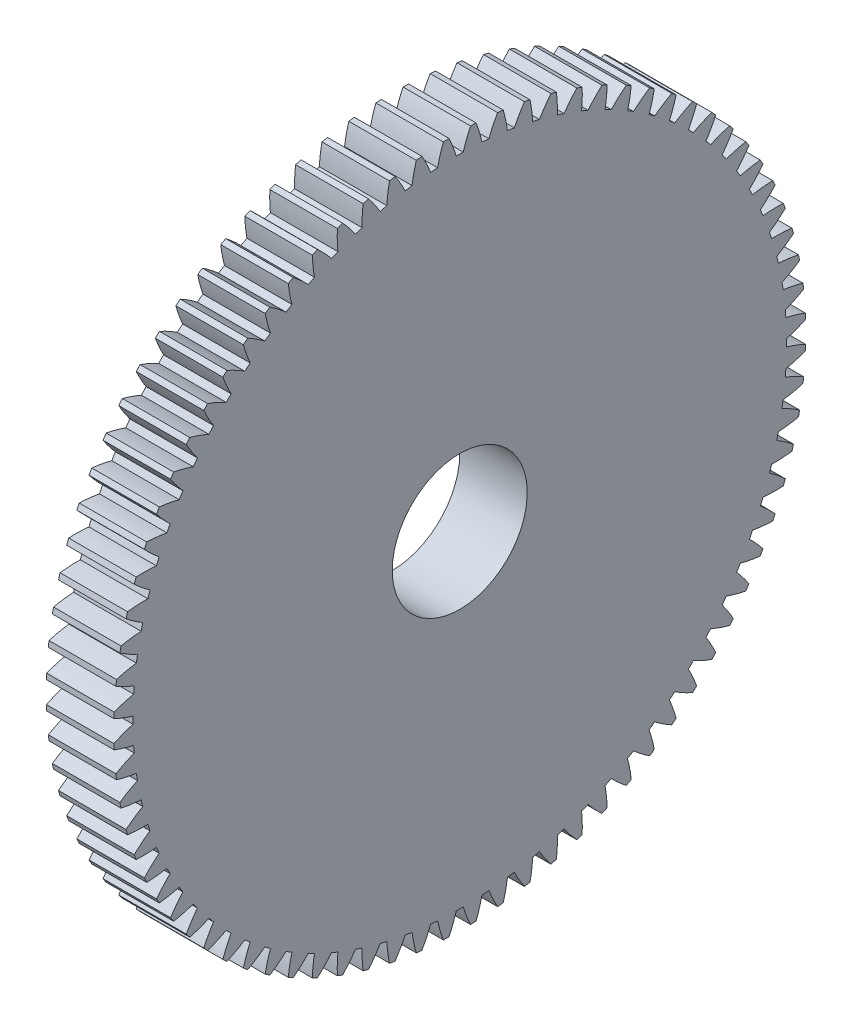
SolidWorks part; units mm, degrees
ref_plane "Plane1" through (0, 0, 0) normal (0, 0, 1) x (1, 0, 0)
ref_plane "Plane2" through (0, 0, 0) normal (0, 1, 0) x (1, 0, 0)
ref_plane "Plane3" through (0, 0, 0) normal (1, 0, 0) x (0, 0, -1)
sketch "HoldingSke" plane through (0, 0, 0) normal (0, 1, 0) x (1, 0, 0)
  line L0 (0, 0) -> (141.1412, -800.4517)
  line L1 (-15, 0) -> (100, 0) construction
  line L2 (0, 0) -> (-2.1039, 2.3779)
  line L3 (0, 0) -> (-11.863, 4.5341)
  line L4 (0, 0) -> (1.4996, 8.5048)
  line L5 (0, 0) -> (-47.5972, -17.7524)
  line L6 (0, 0) -> (-5.2639, -3.5516)
  line L7 (-2.1039, 2.3779) -> (8.8308, 51.9871)
  line L8 (-76.2, 54.61) -> (-61.976, 54.61)
  line L9 (-71.009, 38.7566) -> (-53.1078, 45.2721)
  line L10 (-76.2, 71.12) -> (104.1128, 71.12)
  line L11 (0, 0) -> (-6.35, 0)
  line L12 (-76.2, 101.6) -> (-76.1716, 101.6)
  line L13 (24.9733, 27.94) -> (52.9518, 28.4284)
  line L14 (24.9733, 27.94) -> (25.0241, 27.9398)
  line L15 (24.9733, 27.94) -> (100.4021, 29.52)
  circle A0 centre (0, 0) radius 6.35
  circle A1 centre (0, 0) radius 30.7467
  circle A2 centre (0, 0) radius 38.1
  circle A3 centre (0, 0) radius 6.35
  dimension "MHD" = 61.4934
  dimension "Hub_dia" = 76.2
  dimension "Bore" = 12.7
  dimension "MBD" = 12.7
  dimension "Num_teeth" = 80
  dimension "Pitch" = 812.8
  dimension "Overall_len" = 50.8
  dimension "Show_teeth" = 80
  dimension "Thickness" = 6.35
  dimension "OAL" = 50.8001
  dimension "T_dim" = 14.224
  dimension "Ap" = 20
  dimension "H" = 19.05
  dimension "Pitch_radius" = 180.3128
  dimension "Width" = 6.35
  dimension "Backlash" = 0.0284
  dimension "Addendum_fac" = 1
  dimension "Dedendum_fac" = 1.2
  dimension "Clearance_fac" = 0.2
  dimension "Dedendum_add" = 0.0508
sketch "BasProSke" plane through (0, 0, 0) normal (0, 1, 0) x (1, 0, 0)
  line L0 (-10, 0) -> (60, 0) construction
  line L1 (0, 0) -> (0, 32.5437)
  line L2 (0, 0) -> (6.35, 0)
  line L3 (6.35, 0) -> (6.35, 32.5437)
  line L4 (6.35, 32.5437) -> (0, 32.5437)
  dimension "Thickness" = 6.35
  dimension "Diameter" = 65.0875
revolve "Base-Revolve" add sketch "BasProSke" angle 360 about L0
sketch "TooCutSke" plane through (0, 0, 0) normal (1, 0, 0) x (0, 0, -1)
  line L1 (0, 0) -> (0, 107) construction
  line L2 (0, 0) -> (-0.6732, 31.7429) construction
  line L3 (0, 0) -> (-2.4926, 63.4407) construction
  line L4 (-0.6732, 31.7429) -> (-1.2463, 31.7203) construction
  arc A0 (0.3278, 30.745) -> (-0.3278, 30.745) centre (0, 0) ccw
  arc A1 (1.0248, 32.553) -> (-1.0248, 32.553) centre (0, 0) ccw
  circle A2 centre (0, 0) radius 31.75 construction
  circle A3 centre (0, 0) radius 29.8352 construction
  arc A4 (-0.3278, 30.745) -> (-1.0248, 32.553) centre (-12.4918, 27.0942) ccw
  arc A5 (1.0248, 32.553) -> (0.3278, 30.745) centre (12.4918, 27.0942) ccw
  dimension "Root_dia" = 61.4934
  dimension "Overcut_dia" = 65.1383
  dimension "Pitch_dia" = 63.5
  dimension "Base_dia" = 59.6705
  dimension "Flank_rad" = 12.7
  dimension "Half_ang" = 2.25
  dimension "Half_CT" = 0.5736
extrude "ToothCut" cut sketch "TooCutSke" along normal through all
fillet "Breaks" [suppressed] radius 0.0159
fillet "RootFillets" [suppressed] radius 0.2095
pattern_circular "TeethCuts" count 80 every 4.5 about axis through (-10, 0, 0) along (1, 0, 0) of "ToothCut", "RootFillets", "Breaks"
sketch "HubNeaOneSke" plane through (0, 0, 0) normal (-1, 0, 0) x (0, 0, 1)
  circle A0 centre (0, 0) radius 30.7467
  dimension "Diameter" = 61.4934
extrude "HubNearOne" [suppressed] add sketch "HubNeaOneSke" along normal blind 44.4501
sketch "HubNeaBotSke" plane through (0, 0, 0) normal (-1, 0, 0) x (0, 0, 1)
  circle A0 centre (0, 0) radius 30.7467
  dimension "Diameter" = 61.4934
extrude "HubNearBoth" [suppressed] add sketch "HubNeaBotSke" along normal blind 22.225
ref_plane "FarPln" through (6.35, 0, 0) normal (1, 0, 0) x (0, 0, -1)
sketch "HubFarSke" plane through (6.35, 0, 0) normal (1, 0, 0) x (0, 0, -1)
  circle A0 centre (0, 0) radius 30.7467
  dimension "Diameter" = 61.4934
extrude "HubFar" [suppressed] add sketch "HubFarSke" along normal blind 22.225
sketch "BorSke" plane through (0, 0, 0) normal (1, 0, 0) x (0, 0, -1)
  circle A0 centre (0, 0) radius 6.35
  dimension "Diameter" = 12.7
extrude "Bore" cut sketch "BorSke" along normal mid plane 101.6001
sketch "KeySke" plane through (0, 0, 0) normal (1, 0, 0) x (0, 0, -1)
  line L0 (-1.5875, 0) -> (-1.5875, 7.874)
  line L1 (-1.5875, 7.874) -> (1.5875, 7.874)
  line L2 (1.5875, 7.874) -> (1.5875, 0)
  line L3 (0, 0) -> (0, 34) construction
  line L4 (-1.5875, 0) -> (1.5875, 0)
  dimension "Offset" = 7.874
  dimension "Width" = 3.175
extrude "Keyway" [suppressed] cut sketch "KeySke" along normal mid plane 101.6001
pattern_circular "Keyway2" [suppressed] count 2 every 90 about axis through (-10, 0, 0) along (1, 0, 0)
equation "' \"Pitch@HoldingSke\" = 4"
equation "' \"Num_teeth@HoldingSke\" = 12"
equation "' \"Ap@HoldingSke\" =  20"
equation "' \"Ap@HoldingSke\" = 20"
equation "' \"Width@HoldingSke\" = 0.5"
equation "' \"Hub_dia@HoldingSke\"= 1"
equation "' \"Hub_dia@HoldingSke\" = 1"
equation "' \"Overall_len@HoldingSke\" = 1.0"
equation "' \"Bore@HoldingSke\" = 0.75"
equation "' \"T_dim@HoldingSke\" = 0.85"
equation "' \"Width@KeySke\" = 0.25"
equation "' \"Show_teeth@HoldingSke\" = 13"
equation "' \"Backlash@HoldingSke\" = 0.009"
equation "' \"Addendum_fac@HoldingSke\" = 1.0"
equation "' \"Dedendum_fac@HoldingSke\" = 1.25"
equation "' \"Dedendum_add@HoldingSke\" = 0.00005"
equation "' \"Clearance_fac@HoldingSke\" = 0.25"
equation "' \"Pitch@HoldingSke\" = 0.5"
equation "' \"Num_teeth@HoldingSke\" = 23"
equation "' \"Show_teeth@HoldingSke\" = 23"
equation "' \"Backlash@HoldingSke\" = 0.0375"
equation "\"Overcut_dia@TooCutSke\" = (\"Num_teeth@HoldingSke\" + 2 * \"Addendum_fac@HoldingSke\") / \"Pitch@HoldingSke\" + 0.002"
equation "\"Pitch_dia@TooCutSke\" = \"Num_teeth@HoldingSke\" / \"Pitch@HoldingSke\""
equation "\"Base_dia@TooCutSke\" = \"Num_teeth@HoldingSke\" / \"Pitch@HoldingSke\" * cos((\"Ap@HoldingSke\"  * 3.14159265 / 180))"
equation "\"Root_dia@TooCutSke\" = (\"Num_teeth@HoldingSke\" + 2) / \"Pitch@HoldingSke\" - 2 * (\"Addendum_fac@HoldingSke\" + \"Dedendum_fac@HoldingSke\") / \"Pitch@HoldingSke\" - \"Dedendum_add@HoldingSke\" * 2"
equation "\"Half_ang@TooCutSke\" = 180 / \"Num_teeth@HoldingSke\""
equation "\"Half_CT@TooCutSke\" = \"Num_teeth@HoldingSke\" / \"Pitch@HoldingSke\" * sin((3.14159265 / 2 / \"Num_teeth@HoldingSke\")) / 2 - 7 * \"Backlash@HoldingSke\" / 4"
equation "\"Flank_rad@TooCutSke\" = \"Num_teeth@HoldingSke\" / \"Pitch@HoldingSke\" / 5"
equation "\"Radius@RootFillets\" = \"Clearance_fac@HoldingSke\" / \"Pitch@HoldingSke\" + \"Dedendum_add@HoldingSke\""
equation "\"Break_rad@Breaks\" = 0.02 / \"Pitch@HoldingSke\""
equation "\"Thickness@HoldingSke\" = \"Width@HoldingSke\""
equation "\"OAL@HoldingSke\" = \"Thickness@HoldingSke\""
equation "\"MHD@HoldingSke\" = (\"Num_teeth@HoldingSke\" + 2) / \"Pitch@HoldingSke\" - 2 * (\"Addendum_fac@HoldingSke\" + \"Dedendum_fac@HoldingSke\")  / \"Pitch@HoldingSke\" - \"Dedendum_add@HoldingSke\" * 2"
equation "\"MBD@HoldingSke\" = (\"Num_teeth@HoldingSke\" + 2) / \"Pitch@HoldingSke\" - 2 * (\"Addendum_fac@HoldingSke\" + \"Dedendum_fac@HoldingSke\")  / \"Pitch@HoldingSke\" - \"Dedendum_add@HoldingSke\" * 2 - 0.002"
equation "\"MHD@HoldingSke\" = ((sgn( \"MHD@HoldingSke\" - \"Hub_dia@HoldingSke\" )-1)*( \"MHD@HoldingSke\" - \"Hub_dia@HoldingSke\" ))/-2+ \"Hub_dia@HoldingSke\""
equation "\"MBD@HoldingSke\" = ((sgn( \"MBD@HoldingSke\" - \"Bore@HoldingSke\" )-1)*( \"MBD@HoldingSke\" - \"Bore@HoldingSke\" ))/-2+ \"Bore@HoldingSke\""
equation "\"OAL@HoldingSke\" = ((sgn( \"OAL@HoldingSke\" - \"Overall_len@HoldingSke\" )+1)*( \"OAL@HoldingSke\" - \"Overall_len@HoldingSke\" ))/2 + \"Overall_len@HoldingSke\" + 0.000002"
equation "\"Num_teeth@TeethCuts\" = int( \"Show_teeth@HoldingSke\" ) + 1"
equation "\"Num_teeth@TeethCuts\" = ((sgn( \"Num_teeth@TeethCuts\" - \"Num_teeth@HoldingSke\" )-1)*( \"Num_teeth@TeethCuts\" - \"Num_teeth@HoldingSke\" ))/-2+ \"Num_teeth@HoldingSke\""
equation "\"Num_teeth@TeethCuts\" = ((sgn( \"Num_teeth@TeethCuts\" - 2.0)+1)*( \"Num_teeth@TeethCuts\" - 2.0))/2 +2.0"
equation "\"Angle@TeethCuts\" = 360.0 / \"Num_teeth@HoldingSke\""
equation "\"Diameter@BasProSke\" = (\"Num_teeth@HoldingSke\" + 2 * \"Addendum_fac@HoldingSke\") / \"Pitch@HoldingSke\""
equation "\"Thickness@BasProSke\"  = \"Thickness@HoldingSke\""
equation "' \"Fillet_rad@BasProSke\" =  \"Thickness@HoldingSke\" * 0.05"
equation "' \"Fillet_rad@BasProSke\" = \"Thickness@HoldingSke\" * 0.05"
equation "\"MHD@HoldingSke\" = ((sgn( \"MHD@HoldingSke\" - \"Root_dia@TooCutSke\" )-1)*( \"MHD@HoldingSke\" - \"Root_dia@TooCutSke\" ))/-2+ \"Root_dia@TooCutSke\""
equation "\"Diameter@HubNeaOneSke\" = \"MHD@HoldingSke\""
equation "\"Length@HubNearOne\" = \"OAL@HoldingSke\" - \"Thickness@BasProSke\""
equation "\"Diameter@HubNeaBotSke\" = \"MHD@HoldingSke\""
equation "\"Length@HubNearBoth\" = ( \"OAL@HoldingSke\" - \"Thickness@BasProSke\" ) / 2.0"
equation "\"Thickness@FarPln\" = \"Thickness@BasProSke\""
equation "\"Diameter@HubFarSke\" = \"MHD@HoldingSke\""
equation "\"Length@HubFar\" = ( \"OAL@HoldingSke\" - \"Thickness@BasProSke\" ) / 2.0"
equation "\"Diameter@BorSke\" = \"MBD@HoldingSke\""
equation "\"D1@Bore\" = \"OAL@HoldingSke\" * 2.0"
equation "\"D1@Keyway\" = \"OAL@HoldingSke\" * 2.0"
equation "\"Offset@KeySke\" = \"T_dim@HoldingSke\" - \"MBD@HoldingSke\" / 2.0"
